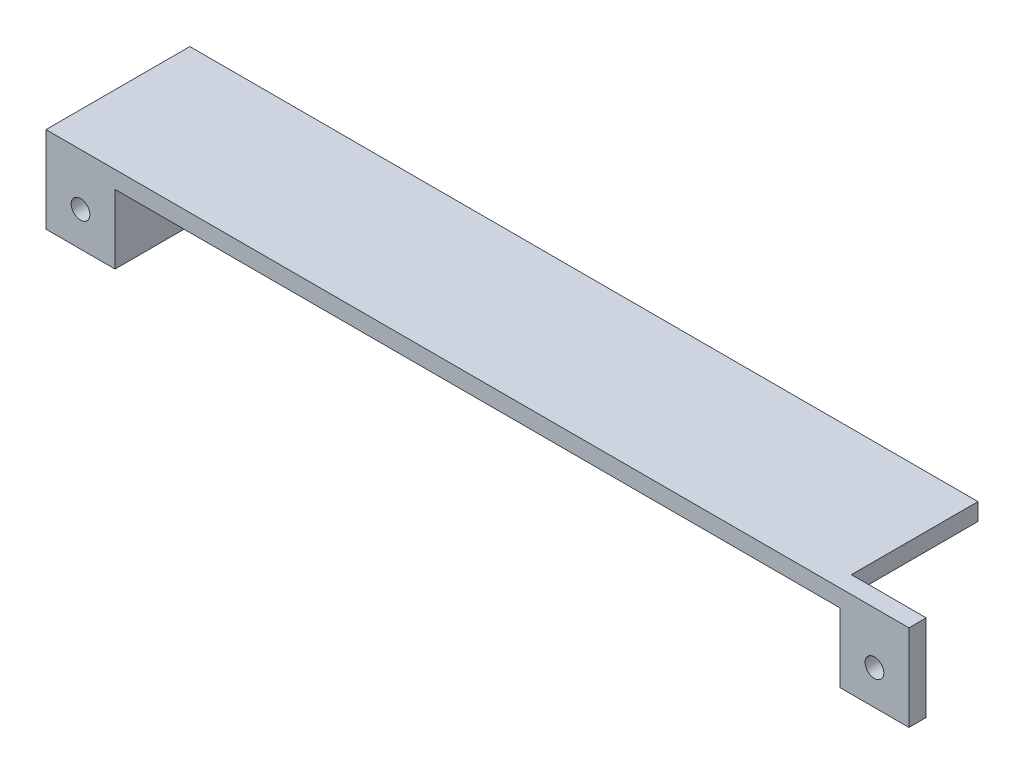
SolidWorks part; units mm, degrees
ref_plane "Front Plane" through (0, 0, 0) normal (0, 0, 1) x (1, 0, 0)
ref_plane "Top Plane" through (0, 0, 0) normal (0, 1, 0) x (1, 0, 0)
ref_plane "Right Plane" through (0, 0, 0) normal (1, 0, 0) x (0, 0, -1)
sketch "Sketch1" plane through (0, 0, 0) normal (0, 1, 0) x (1, 0, 0)
  line L1 (0, 0) -> (150, 0)
  line L2 (0, 0) -> (0, 25)
  line L3 (0, 25) -> (150, 25)
  line L4 (150, 0) -> (150, 25)
  dimension "D1" = 150
  dimension "D2" = 25
extrude "Boss-Extrude1" add sketch "Sketch1" along normal blind 3
sketch "Sketch2" plane through (0, 0, 0) normal (0, -1, 0) x (1, 0, 0)
  line L0 (75, 0) -> (75, -25) construction
  line L1 (0, 0) -> (12, 0)
  line L2 (0, 0) -> (0, -25)
  line L3 (0, -25) -> (12, -25)
  line L4 (12, 0) -> (12, -25)
  line L5 (0, 0) -> (150, 0) construction
  line L6 (150, -25) -> (0, -25) construction
  line L7 (150, -25) -> (138, -25)
  line L8 (138, 0) -> (138, -25)
  line L9 (150, 0) -> (138, 0)
  line L10 (150, 0) -> (150, -25)
  line L11 (0, -12.5) -> (150, -12.5) construction
  line L12 (0, -25) -> (0, 0) construction
  line L13 (150, 0) -> (150, -25) construction
  dimension "D1" = 25
  dimension "D2" = 12
extrude "Boss-Extrude2" add sketch "Sketch2" along normal blind 12
sketch "Sketch4" plane through (0, 0, 0) normal (0, 0, 1) x (1, 0, 0)
  line L0 (12, -12) -> (12, 0) construction
  line L1 (12, -12) -> (0, -12) construction
  line L2 (75, 3) -> (75, 0) construction
  line L3 (0, 3) -> (150, 3) construction
  line L4 (12, 0) -> (138, 0) construction
  circle A0 centre (6, -6) radius 1.625
  circle A1 centre (144, -6) radius 1.625
  dimension "D1" = 3.25
  dimension "D2" = 6
  dimension "D3" = 6
extrude "Cut-Extrude1" cut sketch "Sketch4" against normal through all
sketch "Sketch5" plane through (0, 3, 0) normal (0, 1, 0) x (1, 0, 0)
  line L0 (150, 0) -> (150, 25) construction
  line L1 (150, 3) -> (137, 3)
  line L2 (150, 3) -> (150, 25)
  line L3 (150, 25) -> (137, 25)
  line L4 (137, 3) -> (137, 25)
  line L5 (150, 25) -> (0, 25) construction
  line L6 (0, 0) -> (150, 0) construction
  dimension "D1" = 3
  dimension "D2" = 13
extrude "Cut-Extrude2" cut sketch "Sketch5" against normal through all
